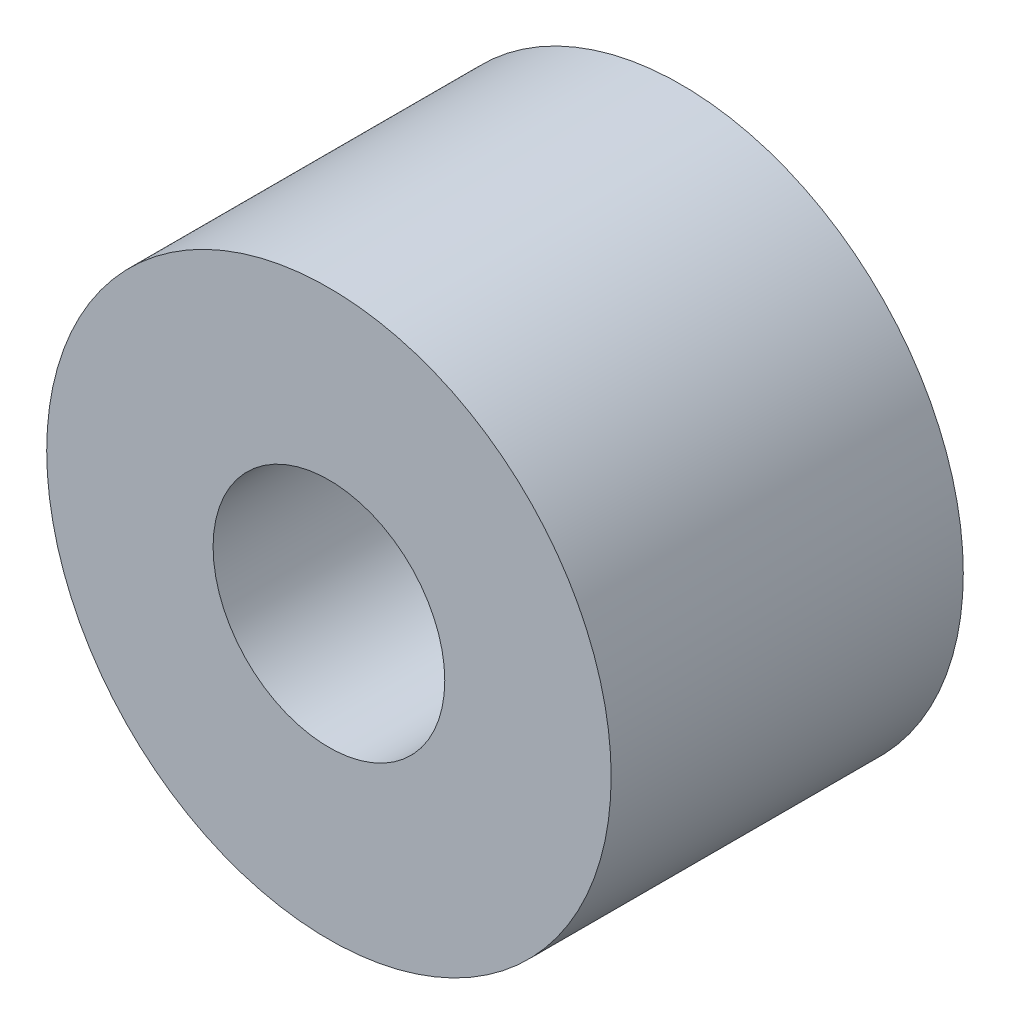
SolidWorks part; units mm, degrees
ref_plane "Alzado" through (0, 0, 0) normal (0, 0, 1) x (1, 0, 0)
ref_plane "Planta" through (0, 0, 0) normal (0, 1, 0) x (1, 0, 0)
ref_plane "Vista lateral" through (0, 0, 0) normal (1, 0, 0) x (0, 0, -1)
sketch "Croquis1" plane through (0, 0, 0) normal (0, 0, 1) x (1, 0, 0)
  circle A0 centre (69.1708, 22.8308) radius 3.5202
  circle A1 centre (69.1708, 22.8308) radius 8.5759
extrude "Saliente-Extruir1" add sketch "Croquis1" along normal blind 10.7
